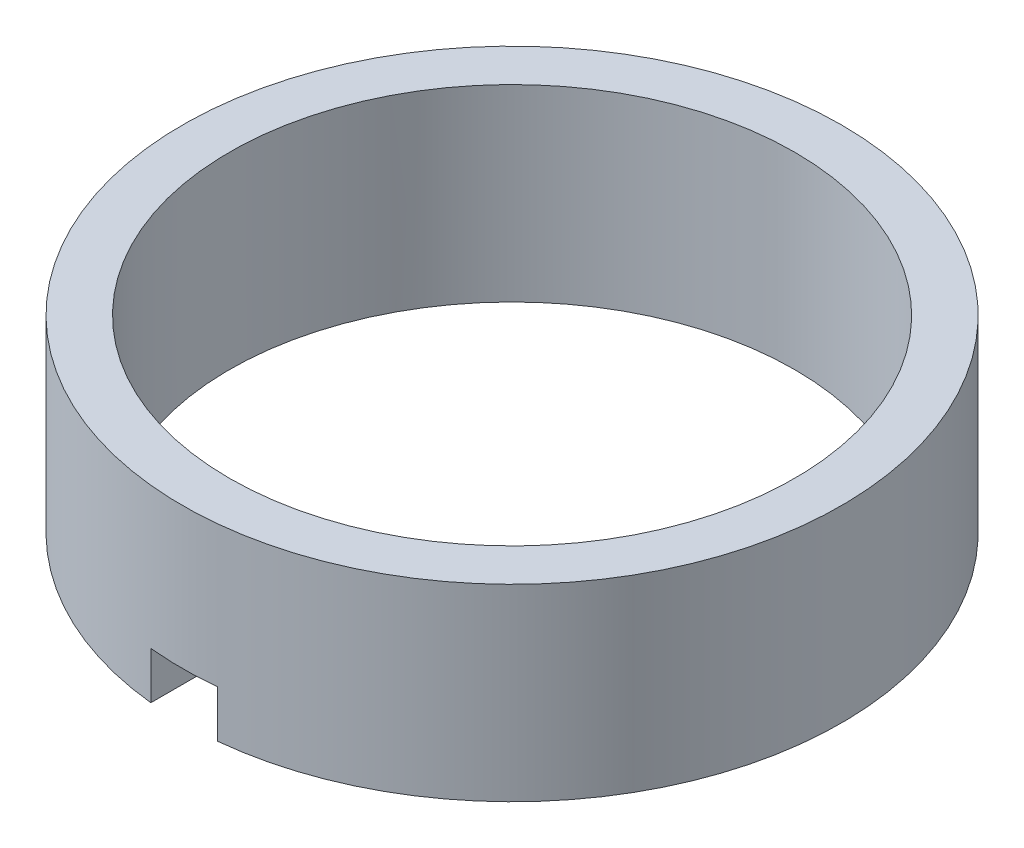
SolidWorks part; units mm, degrees
ref_plane "Front Plane" through (0, 0, 0) normal (1, 0, 0) x (0, 1, 0)
ref_plane "Top Plane" through (0, 0, 0) normal (0, 0, 1) x (0, 1, 0)
ref_plane "Right Plane" through (0, 0, 0) normal (0, 1, 0) x (-1, 0, 0)
sketch "Sketch1" plane through (0, 0, 0) normal (0, 0, 1) x (0, 1, 0)
  line L0 (-38.1, 133.35) -> (38.1, 133.35)
  line L1 (38.1, 133.35) -> (38.1, 114.3254)
  line L2 (38.1, 114.3254) -> (-38.1, 114.3254)
  line L3 (-38.1, 114.3254) -> (-38.1, 133.35)
  line L4 (-63.5, 0) -> (63.5, 0) construction
  dimension "D1" = 76.2
  dimension "D2" = 19.0246
  dimension "D3" = 133.35
revolve "Revolve1" add sketch "Sketch1" angle 360 about L4
sketch "Sketch2" plane through (0, 0, 0) normal (0, 1, 0) x (-1, 0, 0)
  line L1 (-13.4874, 0) -> (13.4874, 0)
  line L2 (-13.4874, 0) -> (-13.4874, 266.7)
  line L3 (-13.4874, 266.7) -> (13.4874, 266.7)
  line L4 (13.4874, 0) -> (13.4874, 266.7)
  dimension "D1" = 26.9748
  dimension "D2" = 266.7
extrude "Cut-Extrude2" cut sketch "Sketch2" along normal blind 19.05 from offset 38.1
